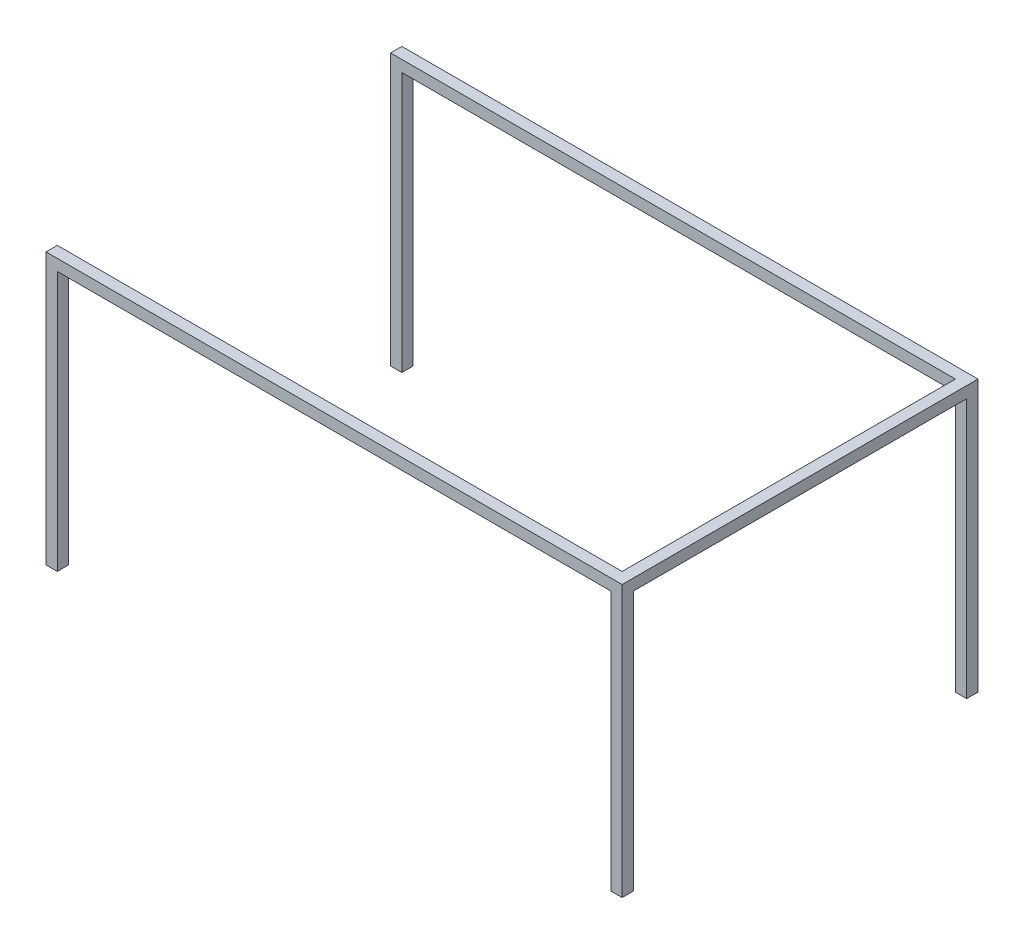
SolidWorks part; units mm, degrees
ref_plane "Front Plane" through (0, 0, 0) normal (0, 0, 1) x (1, 0, 0)
ref_plane "Top Plane" through (0, 0, 0) normal (0, 1, 0) x (1, 0, 0)
ref_plane "Right Plane" through (0, 0, 0) normal (1, 0, 0) x (0, 0, -1)
sketch "Sketch1" plane through (0, 0, 0) normal (0, 1, 0) x (1, 0, 0)
  line L0 (-55, 0) -> (55, 0) construction
  line L1 (-749.3, 374.65) -> (749.3, 374.65) construction
  line L2 (-749.3, 374.65) -> (-749.3, -374.65) construction
  line L3 (-749.3, -374.65) -> (749.3, -374.65) construction
  line L4 (749.3, 374.65) -> (749.3, -374.65) construction
  line L5 (-749.3, 374.65) -> (749.3, -374.65) construction
  line L6 (-749.3, -374.65) -> (749.3, 374.65) construction
  line L7 (749.3, -374.65) -> (-520.7, -374.65)
  line L8 (749.3, -374.65) -> (749.3, -400.05)
  line L9 (749.3, -400.05) -> (-520.7, -400.05)
  line L10 (-520.7, -374.65) -> (-520.7, -400.05)
  line L11 (749.3, 400.05) -> (-520.7, 400.05)
  line L12 (-520.7, 374.65) -> (-520.7, 400.05)
  line L13 (749.3, 374.65) -> (-520.7, 374.65)
  line L14 (749.3, 374.65) -> (749.3, 400.05)
  line L15 (749.3, 400.05) -> (749.3, -400.05)
  line L16 (749.3, 400.05) -> (774.7, 400.05)
  line L17 (749.3, -400.05) -> (774.7, -400.05)
  line L18 (774.7, 400.05) -> (774.7, -400.05)
  point P0 (0, 0)
extrude "Boss-Extrude1" add sketch "Sketch1" along normal blind 25.4 contours L7 L10 L9 L8 | L18 L16 L14 L15 L8 L17
sketch "Sketch2" plane through (0, 0, 0) normal (0, 1, 0) x (1, 0, 0)
  line L0 (749.3, 374.65) -> (-520.7, 374.65) construction
  line L1 (-520.7, 400.05) -> (-495.3, 400.05)
  line L2 (-520.7, 400.05) -> (-520.7, 374.65)
  line L3 (-520.7, 374.65) -> (-495.3, 374.65)
  line L4 (-495.3, 400.05) -> (-495.3, 374.65)
  line L5 (-55, 0) -> (55, 0) construction
  line L6 (774.7, 400.05) -> (749.3, 400.05)
  line L7 (774.7, 400.05) -> (774.7, 374.65)
  line L8 (774.7, 374.65) -> (749.3, 374.65)
  line L9 (749.3, 400.05) -> (749.3, 374.65)
  line L10 (749.3, -400.05) -> (749.3, -374.65)
  line L11 (774.7, -374.65) -> (749.3, -374.65)
  line L12 (774.7, -400.05) -> (774.7, -374.65)
  line L13 (774.7, -400.05) -> (749.3, -400.05)
  line L14 (-495.3, -400.05) -> (-495.3, -374.65)
  line L15 (-520.7, -374.65) -> (-495.3, -374.65)
  line L16 (-520.7, -400.05) -> (-520.7, -374.65)
  line L17 (-520.7, -400.05) -> (-495.3, -400.05)
extrude "Boss-Extrude2" add sketch "Sketch2" against normal blind 584.2
